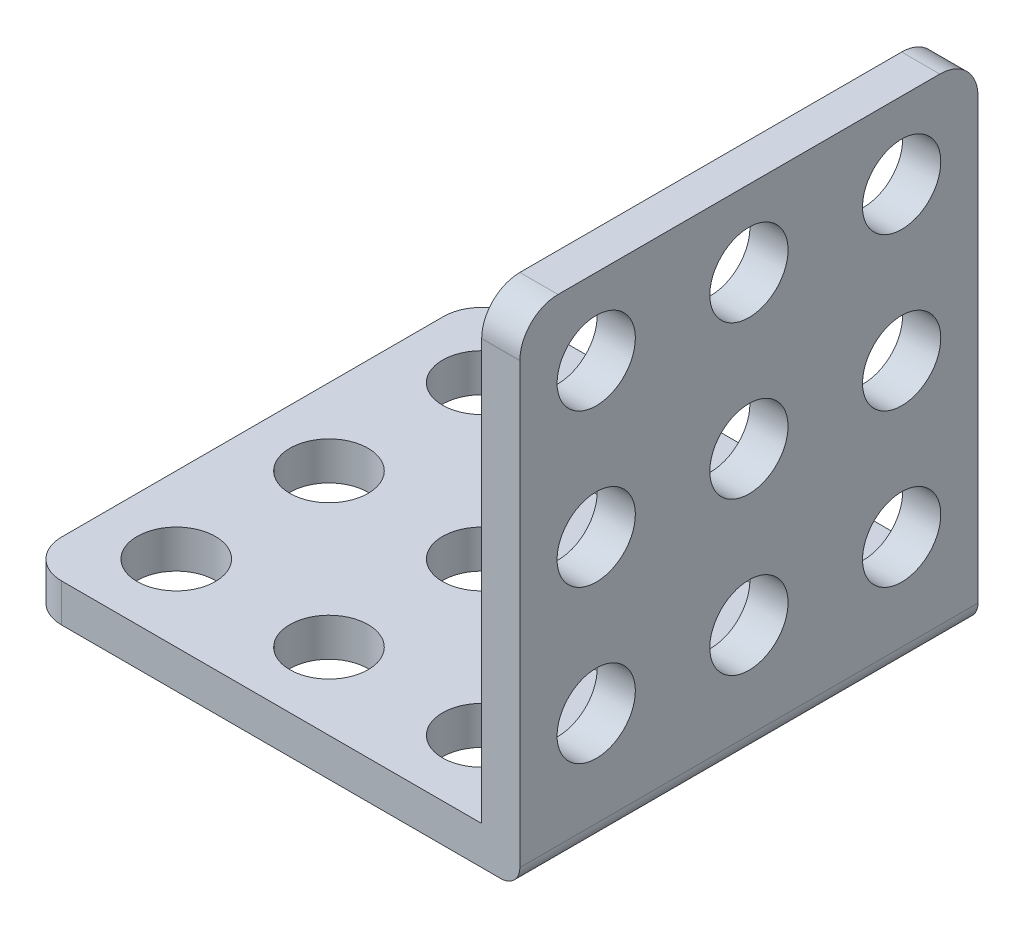
SolidWorks part; units mm, degrees
material "6061-T4 (SS)"
ref_plane "Front Plane" through (0, 0, 0) normal (0, 0, 1) x (1, 0, 0)
ref_plane "Top Plane" through (0, 0, 0) normal (0, 1, 0) x (1, 0, 0)
ref_plane "Right Plane" through (0, 0, 0) normal (1, 0, 0) x (0, 0, -1)
sketch "Sketch1" plane through (0, 0, 0) normal (0, 0, 1) x (1, 0, 0)
  line L0 (-24, 0) -> (0, 0)
  line L1 (0, 0) -> (0, 24)
  line L2 (0, 24) -> (2, 24)
  line L3 (2, 24) -> (2, -2)
  line L4 (2, -2) -> (-24, -2)
  line L5 (-24, -2) -> (-24, 0)
  dimension "D1" = 26
  dimension "D2" = 26
  dimension "D3" = 2
  dimension "D4" = 2
extrude "Boss-Extrude1" add sketch "Sketch1" along normal blind 24
sketch "Sketch2" plane through (0, 0, 0) normal (0, 1, 0) x (1, 0, 0)
  line L0 (-24, -24) -> (-24, 0) construction
  line L1 (0, 0) -> (-24, 0) construction
  line L3 (0, -24) -> (0, 0) construction
  circle A0 centre (-20, -12) radius 2.05
  circle A1 centre (-12, -12) radius 2.05
  circle A2 centre (-20, -4) radius 2.05
  circle A3 centre (-4, -4) radius 2.05
  circle A4 centre (-12, -4) radius 2.05
  circle A5 centre (-4, -12) radius 2.05
  circle A6 centre (-20, -20) radius 2.05
  circle A7 centre (-12, -20) radius 2.05
  circle A8 centre (-4, -20) radius 2.05
  dimension "D2" = 8
  dimension "D6" = 4.1
  dimension "D9" = 4.1
  dimension "D12" = 4.1
  dimension "D3" = 3
  dimension "D7" = 4
  dimension "D8" = 4
  dimension "D10" = 16
  dimension "D11" = 4
extrude "Cut-Extrude1" cut sketch "Sketch2" against normal through all
sketch "Sketch4" plane through (0, 0, 0) normal (-1, 0, 0) x (0, 0, 1)
  line L0 (24, 24) -> (0, 24) construction
  line L2 (24, 24) -> (24, 0) construction
  circle A0 centre (12, 20) radius 2.05
  circle A1 centre (12, 12) radius 2.05
  circle A2 centre (20, 4) radius 2.05
  circle A3 centre (20, 20) radius 2.05
  circle A4 centre (20, 12) radius 2.05
  circle A5 centre (12, 4) radius 2.05
  circle A6 centre (4, 20) radius 2.05
  circle A7 centre (4, 12) radius 2.05
  circle A8 centre (4, 4) radius 2.05
  dimension "D8" = 4.1
  dimension "D10" = 4.1
  dimension "D11" = 4.1
  dimension "D2" = 8
  dimension "D3" = 3
  dimension "D5" = 4
  dimension "D6" = 4
  dimension "D7" = 16
extrude "Cut-Extrude2" cut sketch "Sketch4" against normal through all
fillet "圆角1" radius 1 1 edges at (2, -2, 12)
fillet "圆角2" radius 2 4 edges at (-24, -1, 0) (-24, -1, 24) (1, 24, 24) (1, 24, 0)
